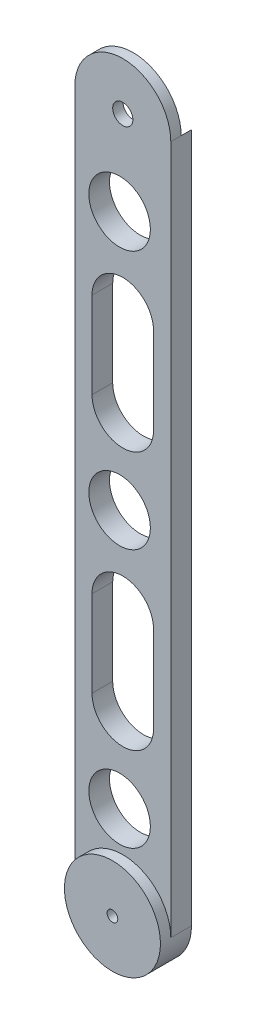
SolidWorks part; units mm, degrees
ref_plane "Plan de face" through (0, 0, 0) normal (0, 0, 1) x (1, 0, 0)
ref_plane "Plan de dessus" through (0, 0, 0) normal (0, 1, 0) x (1, 0, 0)
ref_plane "Plan de droite" through (0, 0, 0) normal (1, 0, 0) x (0, 0, -1)
sketch "Esquisse1" plane through (0, 0, 0) normal (0, 0, 1) x (1, 0, 0)
  line L1 (-9.9585, 27.1869) -> (17.8915, 27.1869)
  line L2 (-9.9585, 27.1869) -> (-9.9585, -172.8131)
  line L3 (-9.9585, -172.8131) -> (17.8915, -172.8131)
  line L4 (17.8915, 27.1869) -> (17.8915, -172.8131)
  arc A0 (-9.9585, -172.8131) -> (17.8915, -172.8131) centre (3.9665, -172.8131) ccw
  arc A1 (17.8915, 27.1869) -> (-9.9585, 27.1869) centre (3.9665, 27.1869) ccw
  dimension "D1" = 27.85
  dimension "D2" = 200
extrude "Boss.-Extru.1" add sketch "Esquisse1" along normal blind 6 contours L4 L1 L2 L3 | L3 A0 | L1 A1
sketch "Esquisse2" plane through (0, 0, 6) normal (0, 0, 1) x (1, 0, 0)
  circle A0 centre (3.9665, -172.8131) radius 13.925
extrude "Enlèv. mat.-Extru.1" cut sketch "Esquisse2" against normal blind 3
sketch "Esquisse3" plane through (0, 0, 3) normal (0, 0, 1) x (1, 0, 0)
  circle A0 centre (3.9665, -172.8131) radius 1.55
  dimension "D1" = 3.1
extrude "Enlèv. mat.-Extru.2" cut sketch "Esquisse3" against normal blind 3
sketch "Esquisse4" plane through (0, 0, 0) normal (0, 0, -1) x (-1, 0, 0)
  circle A0 centre (-3.9665, 27.1869) radius 13.925
sketch "Esquisse5" plane through (0, 0, 6) normal (0, 0, 1) x (1, 0, 0)
  circle A0 centre (3.9665, 27.1869) radius 13.925
sketch "Esquisse6" plane through (0, 0, 0) normal (0, 0, -1) x (-1, 0, 0)
  line L0 (9.9585, 27.1869) -> (9.9585, -172.8131) construction
  line L1 (-12.8915, -22.8131) -> (4.9585, -22.8131)
  line L2 (-12.8915, -22.8131) -> (-12.8915, -47.8131)
  line L3 (-12.8915, -47.8131) -> (4.9585, -47.8131)
  line L4 (4.9585, -22.8131) -> (4.9585, -47.8131)
  line L5 (-12.8915, -97.8131) -> (4.9585, -97.8131)
  line L6 (-12.8915, -97.8131) -> (-12.8915, -122.8131)
  line L7 (-12.8915, -122.8131) -> (4.9585, -122.8131)
  line L8 (4.9585, -97.8131) -> (4.9585, -122.8131)
  line L9 (-17.8915, 27.1869) -> (-17.8915, -172.8131) construction
  circle A0 centre (-3.0406, 2.1869) radius 8.925
  circle A1 centre (-3.0406, -72.8131) radius 8.925
  circle A2 centre (-3.0406, -147.8131) radius 8.925
  arc A3 (-12.8915, -22.8131) -> (4.9585, -22.8131) centre (-3.9665, -22.8131) cw
  arc A4 (4.9585, -47.8131) -> (-12.8915, -47.8131) centre (-3.9665, -47.8131) cw
  arc A5 (-12.8915, -97.8131) -> (4.9585, -97.8131) centre (-3.9665, -97.8131) cw
  arc A6 (4.9585, -122.8131) -> (-12.8915, -122.8131) centre (-3.9665, -122.8131) cw
  circle A7 centre (-3.9665, -172.8131) radius 1.55 construction
  dimension "D3" = 17.85
  dimension "D4" = 17.85
  dimension "D5" = 17.85
  dimension "D1" = 5
  dimension "D2" = 5
  dimension "D6" = 5
  dimension "D7" = 5
  dimension "D8" = 25
  dimension "D9" = 25
  dimension "D10" = 50
  dimension "D11" = 25
  dimension "D12" = 25
  dimension "D13" = 50
  dimension "D14" = 25
extrude "Enlèv. mat.-Extru.4" cut sketch "Esquisse6" against normal blind 10 contours A0 | A3 L1 | L4 L1 L2 L3 | A4 L3 | A1 | L8 L5 L6 L7 | A5 L5 | A6 L7 | A2
sketch "Esquisse7" plane through (0, 0, 0) normal (0, 0, -1) x (-1, 0, 0)
  circle A0 centre (-3.9665, 27.1869) radius 2.925
extrude "Enlèv. mat.-Extru.5" cut sketch "Esquisse7" against normal blind 10
extrude "Enlèv. mat.-Extru.6" cut sketch "Esquisse4" against normal blind 3 contours A0
sketch "Esquisse8" plane through (0, 0, 3) normal (0, 0, 1) x (1, 0, 0)
  circle A0 centre (3.9665, -172.8131) radius 1.55
  circle A1 centre (3.9665, -172.8131) radius 13.925
  dimension "D1" = 3.1
extrude "Boss.-Extru.2" add sketch "Esquisse8" along normal blind 6
sketch "Esquisse9" plane through (0, 0, 0) normal (0, 0, -1) x (-1, 0, 0)
  circle A0 centre (-3.9665, -172.8131) radius 4
  dimension "D1" = 8
extrude "Enlèv. mat.-Extru.7" cut sketch "Esquisse9" against normal blind 2.5
